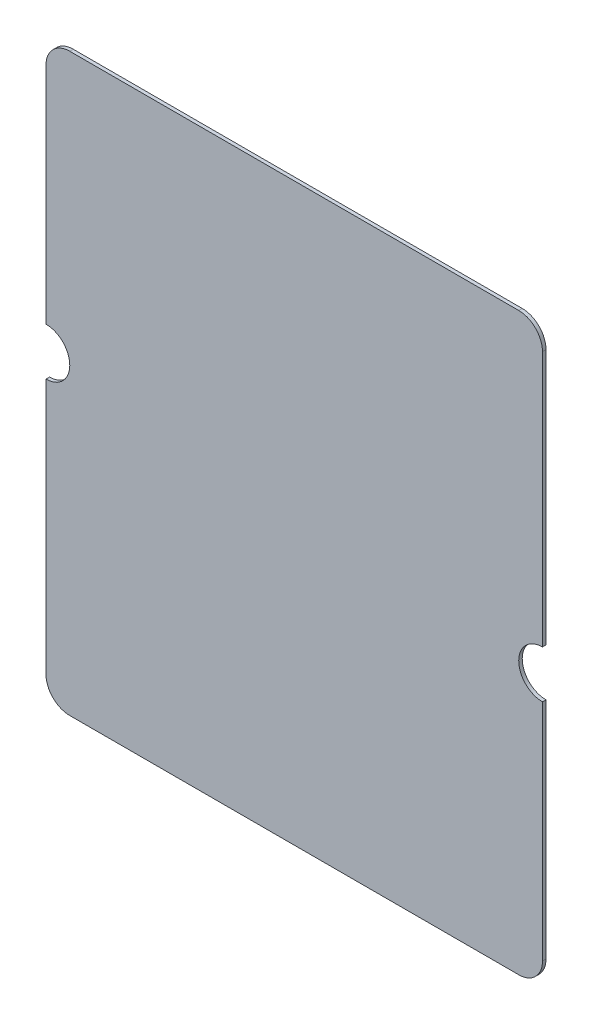
SolidWorks part; units mm, degrees
ref_plane "Front Plane" through (0, 0, 0) normal (0, 0, 1) x (1, 0, 0)
ref_plane "Top Plane" through (0, 0, 0) normal (0, 1, 0) x (1, 0, 0)
ref_plane "Right Plane" through (0, 0, 0) normal (1, 0, 0) x (0, 0, -1)
sketch "Sketch2" plane through (0, 0, 0) normal (0, 0, 1) x (1, 0, 0)
  line L0 (9.5, 0) -> (189, 0)
  line L1 (198.5, 9.5) -> (198.5, 99.25)
  line L2 (198.5, 118.25) -> (198.5, 220.52)
  line L3 (189, 230.02) -> (9.5, 230.02)
  line L4 (0, 220.52) -> (0, 130.77)
  line L5 (0, 111.77) -> (0, 9.5)
  arc A0 (198.5, 118.25) -> (198.5, 99.25) centre (198.5, 108.75) ccw
  arc A1 (0, 130.77) -> (0, 111.77) centre (0, 121.27) cw
  arc A2 (9.5, 0) -> (0, 9.5) centre (9.5, 9.5) cw
  arc A3 (189, 0) -> (198.5, 9.5) centre (189, 9.5) ccw
  arc A4 (189, 230.02) -> (198.5, 220.52) centre (189, 220.52) cw
  arc A5 (9.5, 230.02) -> (0, 220.52) centre (9.5, 220.52) ccw
  point P3 (189, 108.75)
  point P10 (9.5, 121.27)
  point P15 (0, 0)
  point P18 (198.5, 0)
  point P21 (198.5, 230.02)
  point P24 (0, 230.02)
  dimension "D7" = 9.5
  dimension "D12" = 9.5
  dimension "D13" = 9.5
  dimension "D1" = 198.5
  dimension "D2" = 99.25
  dimension "D3" = 9.5
  dimension "D4" = 230.02
  dimension "D5" = 9.5
  dimension "D6" = 9.5
  dimension "D8" = 99.25
  dimension "D9" = 9.5
  dimension "D10" = 9.5
  dimension "D11" = 9.5
extrude "Boss-Extrude1" add sketch "Sketch2" along normal blind 1.4
equation "\"D2@Sketch2\"=108.75-9.5"
equation "\"D5@Sketch2\"=\"D3@Sketch2\""
equation "\"D6@Sketch2\"=\"D3@Sketch2\""
equation "\"D8@Sketch2\"=108.75-9.5"
equation "\"D9@Sketch2\"=\"D3@Sketch2\""
